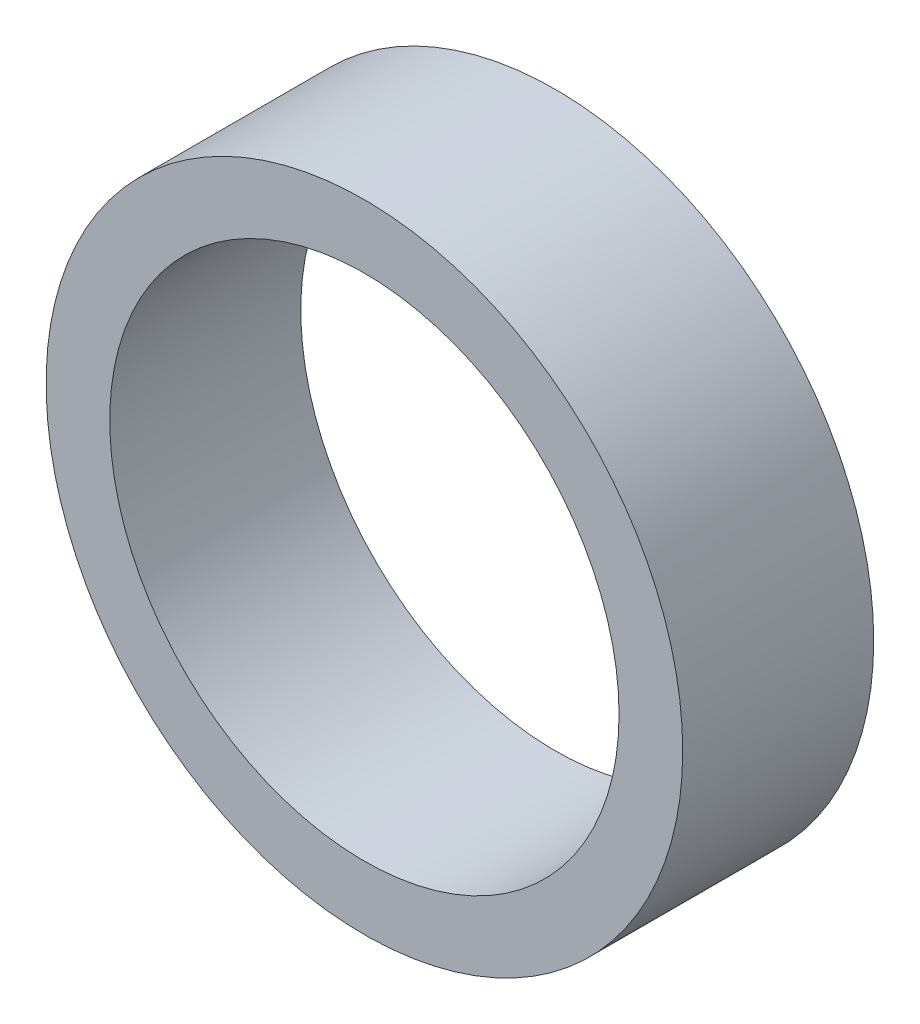
SolidWorks part; units mm, degrees
ref_plane "Front Plane" through (0, 0, 0) normal (0, 0, 1) x (1, 0, 0)
ref_plane "Top Plane" through (0, 0, 0) normal (0, 1, 0) x (1, 0, 0)
ref_plane "Right Plane" through (0, 0, 0) normal (1, 0, 0) x (0, 0, -1)
sketch "Sketch1" plane through (0, 0, 0) normal (0, 0, 1) x (1, 0, 0)
  circle A0 centre (0, 0) radius 50
  circle A1 centre (0, 0) radius 40
extrude "Boss-Extrude1" add sketch "Sketch1" along normal blind 30
